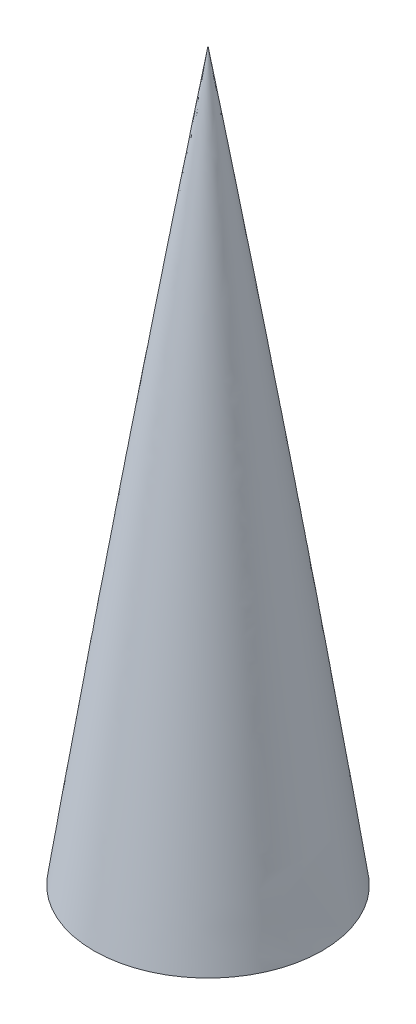
SolidWorks part; units mm, degrees
material "6061-T6 (SS)"
ref_plane "Front Plane" through (0, 0, 0) normal (0, 0, 1) x (1, 0, 0)
ref_plane "Top Plane" through (0, 0, 0) normal (0, 1, 0) x (1, 0, 0)
ref_plane "Right Plane" through (0, 0, 0) normal (1, 0, 0) x (0, 0, -1)
sketch "Sketch1" plane through (0, 0, 0) normal (0, 0, 1) x (1, 0, 0)
  line L0 (0, 0) -> (-49.53, 0) construction
  line L1 (-49.53, 0) -> (-50.8, 0)
  line L2 (-50.8, -33.7223) -> (-50.8, 0) construction
  line L3 (0, 609.6) -> (0, 0) construction
  line L7 (-11.9698, 533.4) -> (0, 533.4)
  line L9 (0, 533.4) -> (0, 609.6)
  arc A0 (-50.8, 0) -> (0, 609.6) centre (3632.2, 0) cw construction
  arc A8 (-11.9698, 533.4) -> (0, 609.6) centre (3632.2, 0) cw
  dimension "D1" = 50.8
  dimension "D2" = 49.53
  dimension "D3" = 609.6
revolve "Revolve1" add sketch "Sketch1" angle 360 about L9
